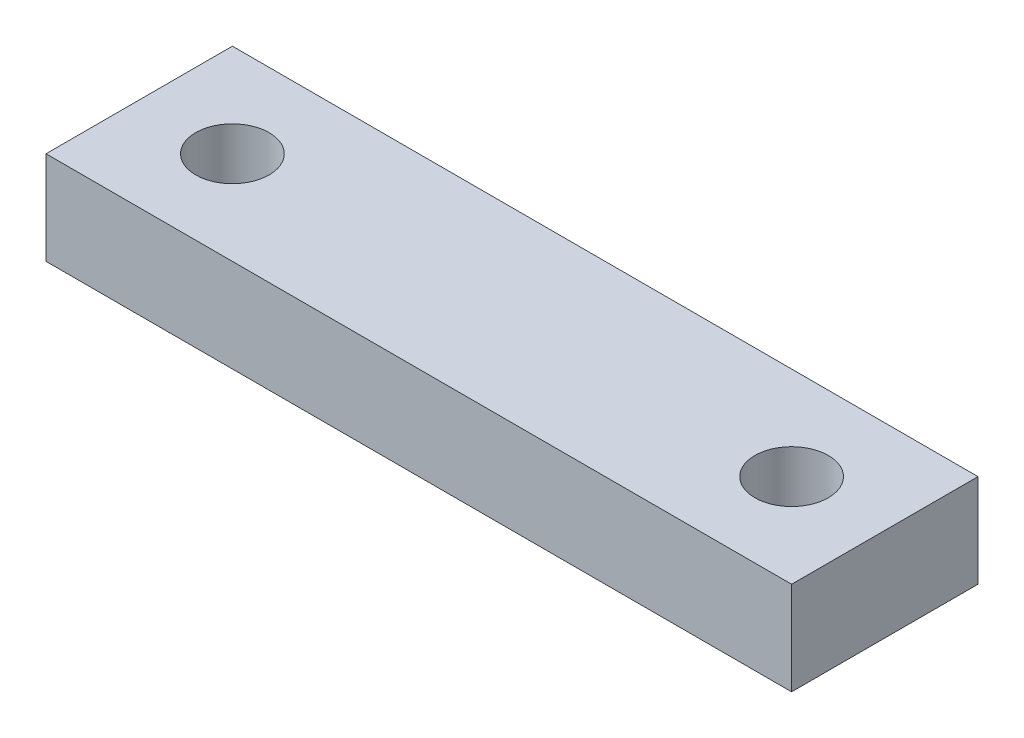
SolidWorks part; units mm, degrees
ref_plane "Front Plane" through (0, 0, 0) normal (0, 0, 1) x (1, 0, 0)
ref_plane "Top Plane" through (0, 0, 0) normal (0, 1, 0) x (1, 0, 0)
ref_plane "Right Plane" through (0, 0, 0) normal (1, 0, 0) x (0, 0, -1)
sketch "Sketch1" plane through (0, 0, 0) normal (0, 1, 0) x (1, 0, 0)
  line L1 (0, 0) -> (50.8, 0)
  line L2 (0, 0) -> (0, 12.7)
  line L3 (0, 12.7) -> (50.8, 12.7)
  line L4 (50.8, 0) -> (50.8, 12.7)
  dimension "D1" = 12.7
  dimension "D2" = 50.8
extrude "Boss-Extrude1" add sketch "Sketch1" along normal blind 6.35
hole_wizard "Ø5.0mm Dowel Hole1" positions "Sketch2" profile "Sketch3" hole size "Ø5.0" standard "ANSI Metric" end condition through all
sketch "Sketch2" plane through (0, 6.35, 0) normal (0, 1, 0) x (1, 0, 0)
  line L0 (0, 12.7) -> (0, 0) construction
  line L1 (50.8, 0) -> (50.8, 12.7) construction
  point P0 (6.35, 6.35)
  point P2 (44.45, 6.35)
  point P11 (0, 6.35)
  dimension "D1" = 6.35
  dimension "D2" = 6.35
sketch "Sketch3" plane through (6.35, 6.35, -6.35) normal (1, 0, 0) x (0, 0, 1)
  line L0 (0, 0) -> (0, 6.35)
  line L1 (0, 6.35) -> (2.5, 6.35)
  line L2 (2.5, 6.35) -> (2.5, 0)
  line L5 (2.5, 0) -> (0, 0)
  line L11 (0, -6.35) -> (0, 107.95) construction
  dimension "Thru Hole Dia." = 5
  dimension "Thru Hole Depth" = 6.35
